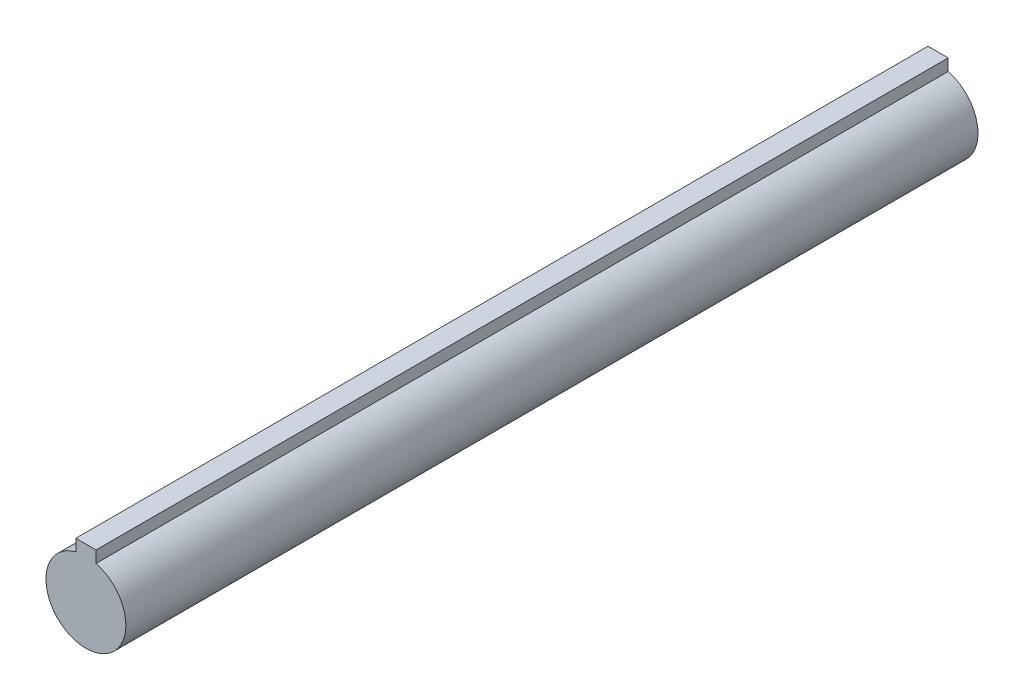
SolidWorks part; units mm, degrees
ref_plane "Front Plane" through (0, 0, 0) normal (0, 0, 1) x (1, 0, 0)
ref_plane "Top Plane" through (0, 0, 0) normal (0, 1, 0) x (1, 0, 0)
ref_plane "Right Plane" through (0, 0, 0) normal (1, 0, 0) x (0, 0, -1)
sketch "Sketch1" plane through (0, 0, 0) normal (0, 0, 1) x (1, 0, 0)
  line L0 (0, 0) -> (0, 13.7617) construction
  line L1 (-2.413, 9.2143) -> (-2.413, 12.0083)
  line L2 (-2.413, 12.0083) -> (2.413, 12.0083)
  line L3 (2.413, 12.0083) -> (2.413, 9.2143)
  arc A0 (-2.413, 9.2143) -> (2.413, 9.2143) centre (0, 0) ccw
  dimension "D1" = 19.05
  dimension "D2" = 2.794
  dimension "D3" = 4.826
extrude "Boss-Extrude1" add sketch "Sketch1" along normal blind 203.2
